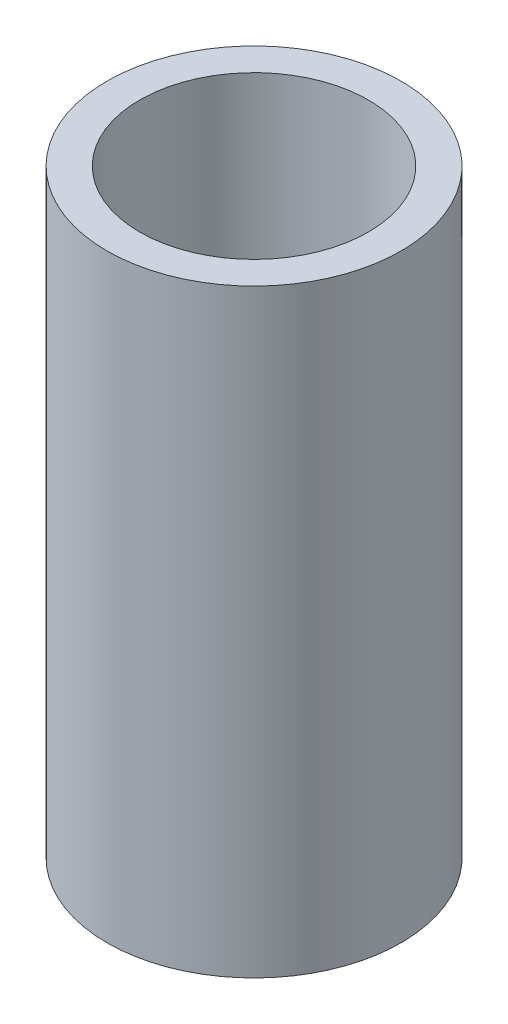
SolidWorks part; units mm, degrees
ref_plane "Front Plane" through (0, 0, 0) normal (0, 0, 1) x (1, 0, 0)
ref_plane "Top Plane" through (0, 0, 0) normal (0, 1, 0) x (1, 0, 0)
ref_plane "Right Plane" through (0, 0, 0) normal (1, 0, 0) x (0, 0, -1)
sketch "Sketch1" plane through (0, 0, 0) normal (0, 1, 0) x (1, 0, 0)
  circle A0 centre (0, 0) radius 2.667
  circle A1 centre (0, 0) radius 3.429
  dimension "D1" = 5.334
  dimension "D2" = 6.858
extrude "Boss-Extrude1" add sketch "Sketch1" along normal blind 13.97
